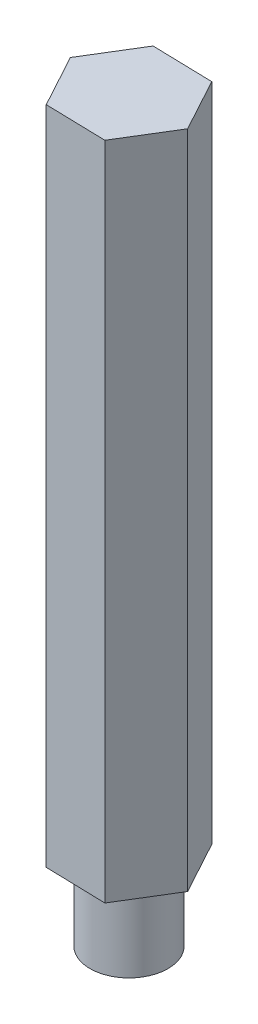
SolidWorks part; units mm, degrees
ref_plane "Alzado" through (0, 0, 0) normal (0, 0, 1) x (1, 0, 0)
ref_plane "Planta" through (0, 0, 0) normal (0, 1, 0) x (1, 0, 0)
ref_plane "Vista lateral" through (0, 0, 0) normal (1, 0, 0) x (0, 0, -1)
sketch "Croquis1" plane through (0, 0, 0) normal (0, 1, 0) x (1, 0, 0)
  line L1 (3.5023, -6.4418) -> (7.3299, -0.1879)
  line L2 (7.3299, -0.1879) -> (3.8277, 6.254)
  line L3 (3.8277, 6.254) -> (-3.5023, 6.4418)
  line L4 (-3.5023, 6.4418) -> (-7.3299, 0.1879)
  line L5 (-7.3299, 0.1879) -> (-3.8277, -6.254)
  line L6 (-3.8277, -6.254) -> (3.5023, -6.4418)
  circle A0 centre (0, 0) radius 6.35 construction
  dimension "D1" = 12.7
extrude "Saliente-Extruir1" add sketch "Croquis1" along normal blind 90
sketch "Croquis2" plane through (0, 0, 0) normal (0, -1, 0) x (1, 0, 0)
  circle A0 centre (0, 0) radius 4.75
  dimension "D1" = 9.5
extrude "Cortar-Extruir1" cut sketch "Croquis2" against normal blind 9.525 flip side to cut
